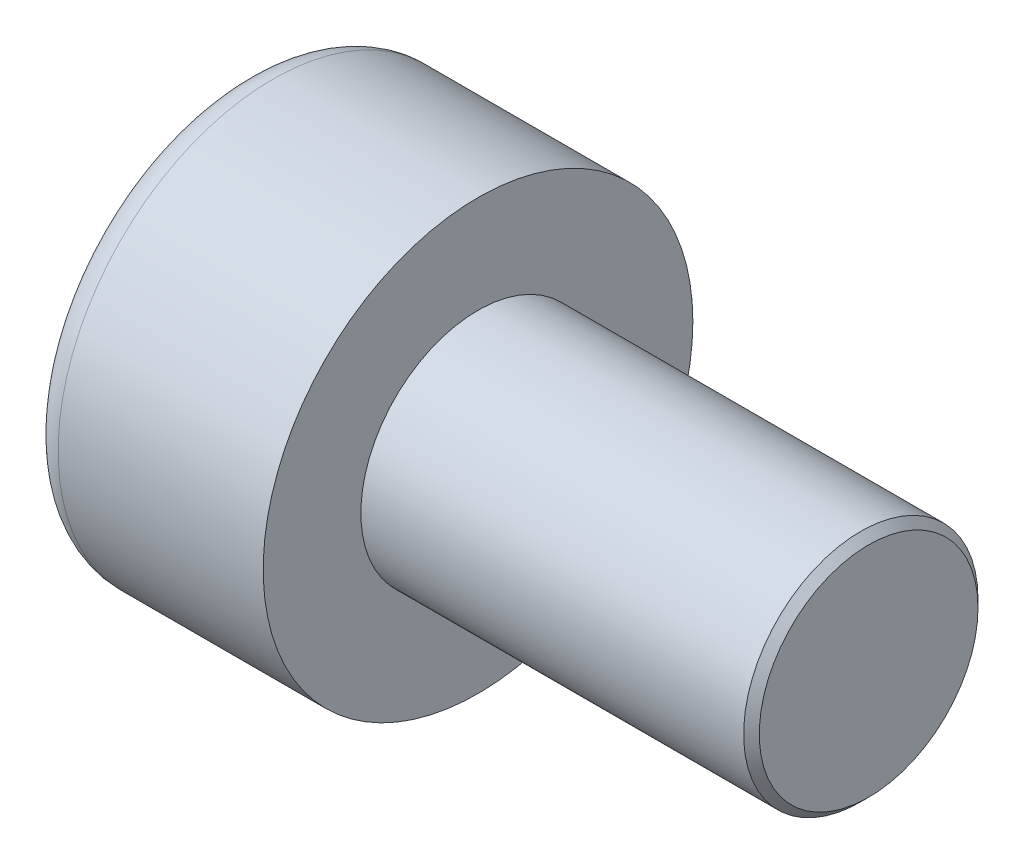
SolidWorks part; units mm, degrees
ref_plane "Front" through (0, 0, 0) normal (0, 0, 1) x (1, 0, 0)
ref_plane "Top" through (0, 0, 0) normal (0, 1, 0) x (1, 0, 0)
ref_plane "Right" through (0, 0, 0) normal (1, 0, 0) x (0, 0, -1)
sketch "Sketch1" plane through (0, 0, 0) normal (1, 0, 0) x (0, 0, -1)
  circle A0 centre (0, 0) radius 2.75
  dimension "dk" = 5.5
extrude "BaseHead" add sketch "Sketch1" along normal blind 3
sketch "Sketch2" plane through (3, 0, 0) normal (1, 0, 0) x (0, 0, -1)
  circle A0 centre (0, 0) radius 1.5
  dimension "d" = 3
extrude "BaseBody" add sketch "Sketch2" along normal blind 5
cosmetic thread "ThreadCosmetic1" [suppressed] parameters "b"=5, "D2"=2.459
sketch "Sketch3" plane through (0, 0, 0) normal (1, 0, 0) x (0, 0, -1)
  line L1 (1.4434, 0) -> (0.7217, 1.25)
  line L2 (0.7217, 1.25) -> (-0.7217, 1.25)
  line L3 (-0.7217, 1.25) -> (-1.4434, 0)
  line L4 (-1.4434, 0) -> (-0.7217, -1.25)
  line L5 (-0.7217, -1.25) -> (0.7217, -1.25)
  line L6 (0.7217, -1.25) -> (1.4434, 0)
  circle A0 centre (0, 0) radius 1.25 construction
  dimension "s" = 2.5
  dimension "e" = 2.8868
extrude "HexagonSocket" cut sketch "Sketch3" along normal blind 1.3
sketch "Sketch4" plane through (-4.1961, 0.75, 0) normal (0, 0, 1) x (-1, 0, 0)
  line L0 (-5.4961, 2) -> (-6.2178, 0.75)
  line L2 (-6.2178, 0.75) -> (-5.4961, 0.75)
  line L3 (-5.4961, 0.75) -> (-5.4961, 2)
  line L4 (-5.0351, 0.75) -> (0.839, 0.75) construction
  line L5 (-12.1961, 0.75) -> (-7.1961, 0.75) construction
  line L6 (-7.1961, 0.75) -> (-4.1961, 0.75) construction
  dimension "m" = 60
revolve "Cut-Revolve1" cut sketch "Sketch4" angle 360 about L4
fillet "HeadFillet" [suppressed] radius 0.1
fillet "TopFillet" radius 0.375 1 edges at (0, 0, -2.75)
chamfer "Chamfer1" distance 0.1 angle 45 1 edges at (8, 0, -1.5)
sketch "Sketch5" plane through (0, 0, 0) normal (0, 0, 1) x (1, 0, 0)
  line L0 (7.9, 1.2657) -> (8.0352, 1.5)
  line L1 (8.0352, 1.5) -> (8.0352, 1.7705)
  line L2 (8.0352, 1.7705) -> (7.7647, 1.7705)
  line L3 (7.7647, 1.7705) -> (7.7647, 1.5)
  line L4 (7.7647, 1.5) -> (7.9, 1.2657)
  line L5 (0, 0) -> (7.8886, 0) construction
  line L6 (7.9, -1.5) -> (7.9, 1.5) construction
  dimension "D1" = 3
  dimension "D2" = 0.2705
revolve "Cut-Revolve10" [suppressed] cut sketch "Sketch5" angle 360 about L5
pattern_linear "LPattern10" [suppressed] count 31 spacing 0.3246 along (1, 0, 0)
equation "\"r1@TopFillet\" = \"d@Sketch2\" / 8"
equation "\"D1@Chamfer1\" = \"r@HeadFillet\""
equation "\"D1@Sketch5\" = \"d@Sketch2\""
equation "\"D2@Sketch5\" =  ( \"d@Sketch2\" - \"D2@ThreadCosmetic1\" )  / 2"
equation "\"D3@LPattern10\" = \"D2@Sketch5\" * 1.2"
equation "\"D1@LPattern10\" = \"b@ThreadCosmetic1\" / \"D3@LPattern10\""
